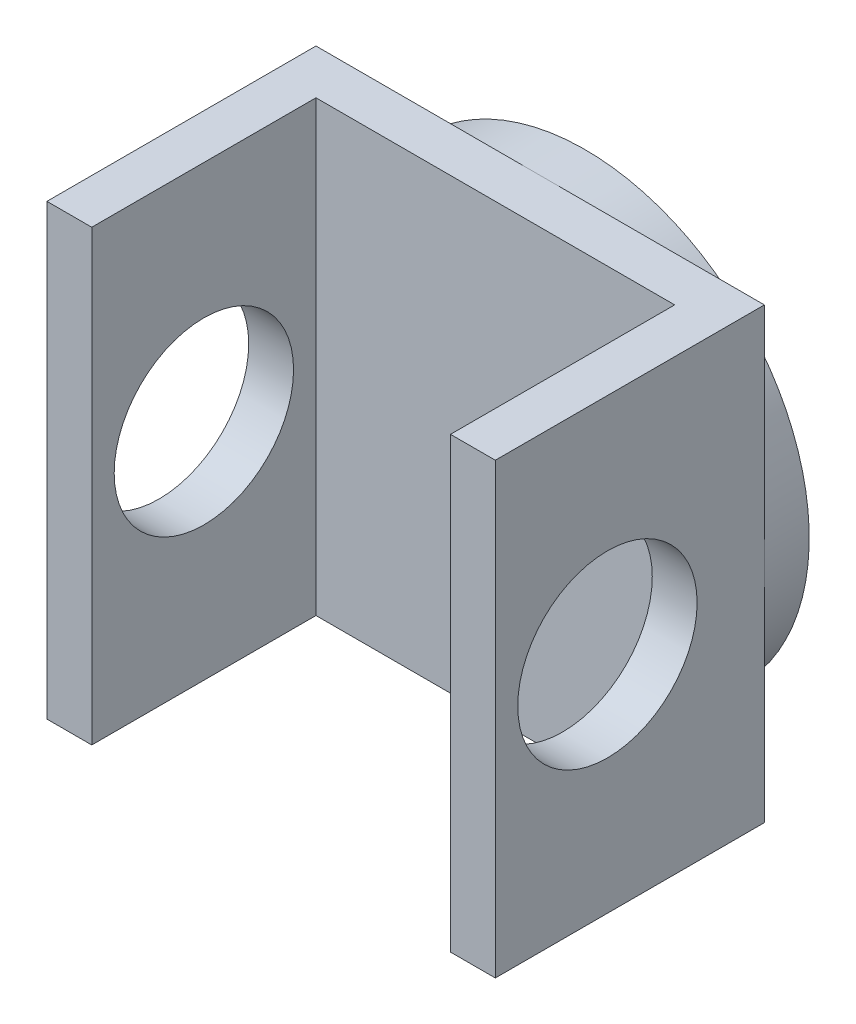
SolidWorks part; units mm, degrees
ref_plane "Front Plane" through (0, 0, 0) normal (0, 0, 1) x (1, 0, 0)
ref_plane "Top Plane" through (0, 0, 0) normal (0, 1, 0) x (1, 0, 0)
ref_plane "Right Plane" through (0, 0, 0) normal (1, 0, 0) x (0, 0, -1)
sketch "Sketch1" plane through (0, 0, 0) normal (0, 0, 1) x (1, 0, 0)
  line L1 (5, -5) -> (-5, -5)
  line L2 (5, -5) -> (5, 5)
  line L3 (5, 5) -> (-5, 5)
  line L4 (-5, -5) -> (-5, 5)
  line L5 (5, -5) -> (-5, 5) construction
  line L6 (5, 5) -> (-5, -5) construction
  point P0 (0, 0)
  dimension "D1" = 10
  dimension "D2" = 10
extrude "Boss-Extrude1" add sketch "Sketch1" along normal blind 1
sketch "Sketch2" plane through (0, 0, 1) normal (0, 0, 1) x (1, 0, 0)
  line L0 (0, 0) -> (0, 3.0567) construction
  line L1 (-4, -5) -> (-5, -5)
  line L2 (-4, -5) -> (-4, 5)
  line L3 (-4, 5) -> (-5, 5)
  line L4 (-5, -5) -> (-5, 5)
  line L5 (-4, -5) -> (-5, 5) construction
  line L6 (-4, 5) -> (-5, -5) construction
  line L7 (4, 5) -> (5, -5) construction
  line L8 (4, -5) -> (5, 5) construction
  line L9 (5, -5) -> (5, 5)
  line L10 (4, 5) -> (5, 5)
  line L11 (4, -5) -> (4, 5)
  line L12 (4, -5) -> (5, -5)
  point P0 (-4.5, 0)
  point P13 (4.5, 0)
  dimension "D1" = 1
extrude "Boss-Extrude2" add sketch "Sketch2" along normal blind 5
sketch "Sketch3" plane through (5, 0, 0) normal (1, 0, 0) x (0, 0, -1)
  line L0 (-6, -5) -> (-6, 5) construction
  circle A0 centre (-3.5, 0) radius 2
  dimension "D1" = 4
  dimension "D2" = 2.5
extrude "Cut-Extrude1" cut sketch "Sketch3" against normal blind 12
sketch "Sketch4" plane through (0, 0, 0) normal (0, 0, -1) x (-1, 0, 0)
  circle A0 centre (0, 0) radius 4
  circle A1 centre (0, 0) radius 5
  dimension "D1" = 8
  dimension "D2" = 1
extrude "Boss-Extrude3" add sketch "Sketch4" along normal blind 1
